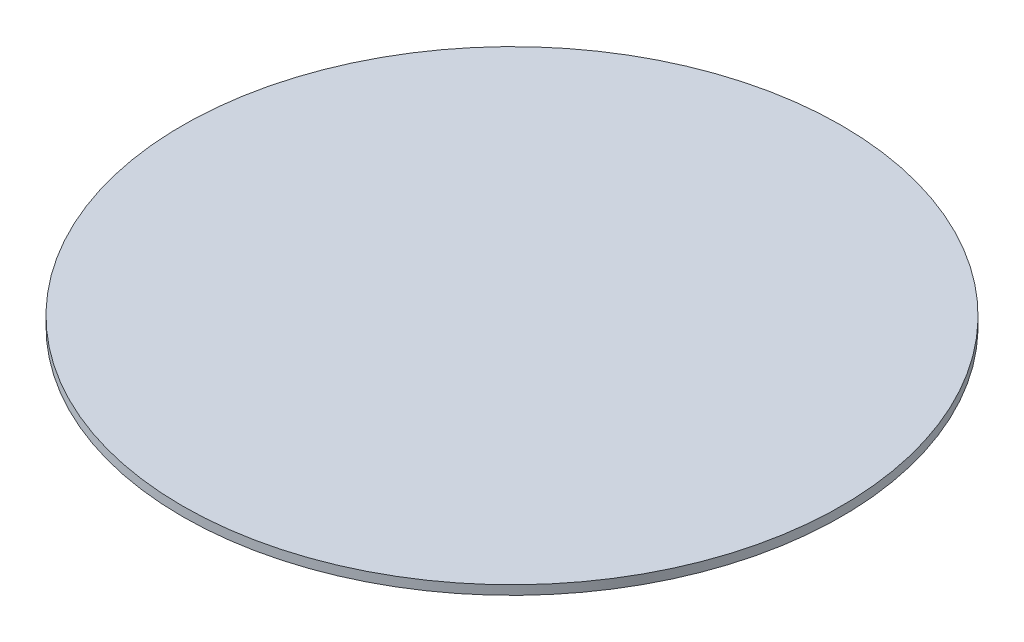
SolidWorks part; units mm, degrees
ref_plane "Front Plane" through (0, 0, 0) normal (0, 0, 1) x (1, 0, 0)
ref_plane "Top Plane" through (0, 0, 0) normal (0, 1, 0) x (1, 0, 0)
ref_plane "Right Plane" through (0, 0, 0) normal (1, 0, 0) x (0, 0, -1)
sketch "Sketch1" plane through (0, 0, 0) normal (0, 1, 0) x (1, 0, 0)
  circle A0 centre (0, 0) radius 107.5
  dimension "D1" = 215
extrude "Boss-Extrude1" add sketch "Sketch1" along normal blind 3
